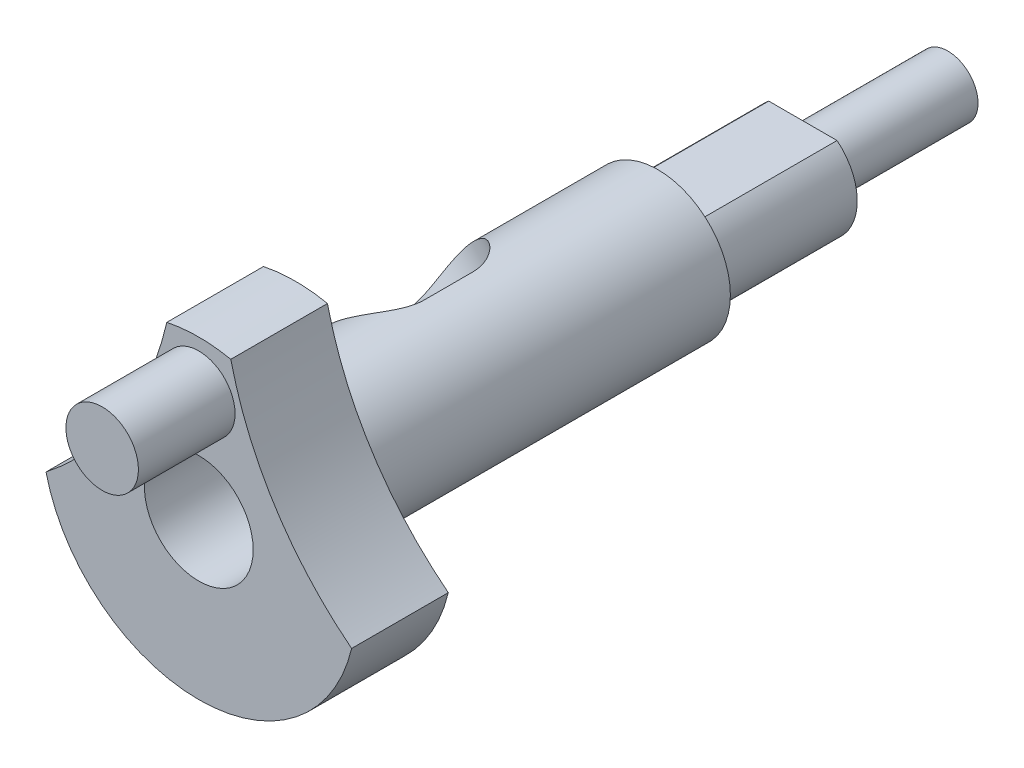
SolidWorks part; units mm, degrees
material "Plain Carbon Steel"
ref_plane "Front Plane" through (0, 0, 0) normal (0, 0, 1) x (1, 0, 0)
ref_plane "Top Plane" through (0, 0, 0) normal (0, 1, 0) x (1, 0, 0)
ref_plane "Right Plane" through (0, 0, 0) normal (1, 0, 0) x (0, 0, -1)
sketch "Sketch1" plane through (0, 0, 0) normal (0, 0, 1) x (1, 0, 0)
  circle A0 centre (0, 0) radius 6
  dimension "D1" = 12
extrude "Boss-Extrude1" add sketch "Sketch1" along normal blind 38
sketch "Sketch2" plane through (0, 0, 0) normal (0, 0, -1) x (-1, 0, 0)
  circle A0 centre (0, 0) radius 4.5
  dimension "D1" = 9
extrude "Boss-Extrude2" add sketch "Sketch2" along normal blind 12
sketch "Sketch3" plane through (0, 0, 38) normal (0, 0, 1) x (1, 0, 0)
  line L0 (12.6491, -3) -> (12.6491, 13) construction
  line L1 (12.6491, 13) -> (-12.6491, 13) construction
  line L2 (-12.6491, 13) -> (-12.6491, -3) construction
  line L3 (0, 0) -> (0, 13) construction
  arc A0 (-12.6491, -3) -> (12.6491, -3) centre (0, 0) ccw
  arc A1 (-12.6491, -3) -> (-2.6491, 12.7272) centre (-29.9303, 19.0309) ccw
  arc A2 (2.6491, 12.7272) -> (-2.6491, 12.7272) centre (0, 0) ccw
  arc A3 (2.6491, 12.7272) -> (12.6491, -3) centre (29.9303, 19.0309) ccw
  point P5 (0, 0)
  dimension "D1" = 26
  dimension "D5" = 13
  dimension "D8" = 28
  dimension "D10" = 28
  dimension "D2" = 13
  dimension "D3" = 16
  dimension "D4" = 16
  dimension "D6" = 10
  dimension "D7" = 10
  dimension "D9" = 13
extrude "Boss-Extrude3" add sketch "Sketch3" against normal blind 8 contours A0 A3 A2 A1
sketch "Sketch4" plane through (0, 0, 38) normal (0, 0, 1) x (1, 0, 0)
  circle A0 centre (0, 9) radius 3
  dimension "D1" = 6
  dimension "D2" = 9
extrude "Boss-Extrude4" add sketch "Sketch4" along normal blind 8 contours A0
sketch "Sketch5" plane through (0, 0, 38) normal (0, 0, 1) x (1, 0, 0)
  circle A0 centre (0, 0) radius 4.5
  dimension "D1" = 9
extrude "Cut-Extrude1" cut sketch "Sketch5" against normal blind 27
ref_plane "Plane1" through (-4.2426, 4.2426, 0) normal (-0.7071, 0.7071, 0) x (0, 0, -1)
sketch "Sketch6" plane through (-4.2426, 4.2426, 0) normal (-0.7071, 0.7071, 0) x (0, 0, -1)
  line L0 (-30, 0) -> (0, 0) construction
  line L1 (-30, -6) -> (-30, 6) construction
  line L2 (-19, 0) -> (-15, 0) construction
  line L3 (-19, 4) -> (-15, 4)
  line L4 (-19, -4) -> (-15, -4)
  arc A0 (-19, 4) -> (-19, -4) centre (-19, 0) ccw
  arc A1 (-15, -4) -> (-15, 4) centre (-15, 0) ccw
  point P7 (-17, 0)
  dimension "D1" = 8
  dimension "D2" = 4
  dimension "D3" = 13
extrude "Cut-Extrude2" cut sketch "Sketch6" against normal blind 5
sketch "Sketch7" plane through (0, 0, -12) normal (0, 0, -1) x (-1, 0, 0)
  circle A0 centre (0, 0) radius 2.5
  dimension "D1" = 5
extrude "Boss-Extrude5" add sketch "Sketch7" along normal blind 12
sketch "Sketch9" plane through (0, 0, 0) normal (1, 0, 0) x (0, 0, -1)
  line L0 (0, 6.6) -> (0, -6.6) construction
  line L1 (12, 4.5) -> (0, 4.5)
  line L2 (12, 4.5) -> (12, 3.5)
  line L3 (12, 3.5) -> (0, 3.5)
  line L4 (0, 4.5) -> (0, 3.5)
  dimension "D1" = 1
extrude "Cut-Extrude3" cut sketch "Sketch9" against normal mid plane 7
